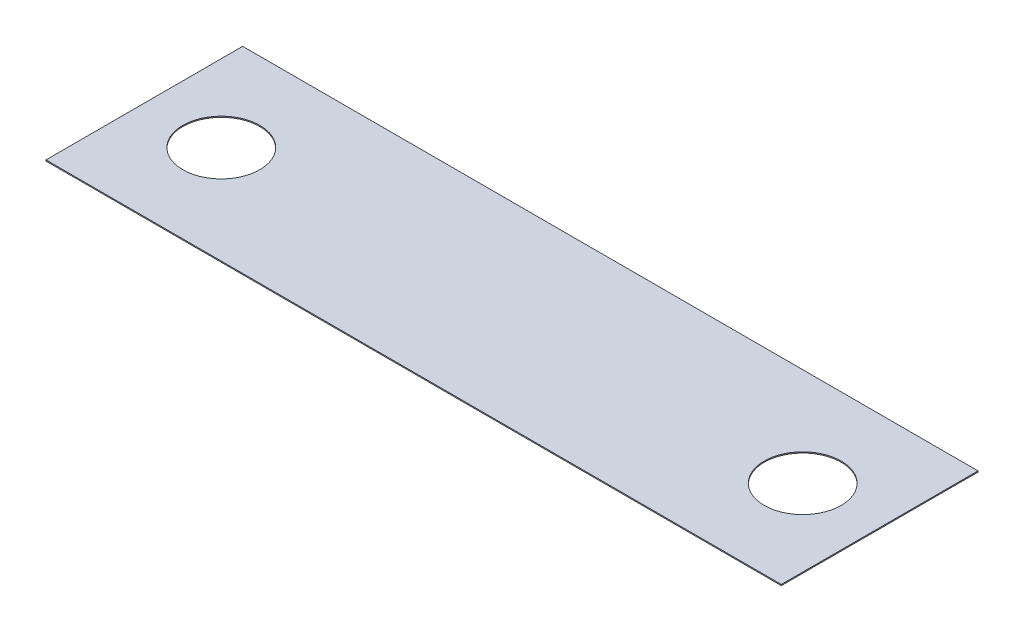
SolidWorks part; units mm, degrees
material "Low Carbon Cold Rolled"
ref_plane "Front Plane" through (0, 0, 0) normal (0, 0, 1) x (1, 0, 0)
ref_plane "Top Plane" through (0, 0, 0) normal (0, 1, 0) x (1, 0, 0)
ref_plane "Right Plane" through (0, 0, 0) normal (1, 0, 0) x (0, 0, -1)
sketch "Sketch1" plane through (0, 0, 0) normal (0, 1, 0) x (1, 0, 0)
  line L1 (0, 0) -> (86, 0)
  line L2 (0, 0) -> (0, 23)
  line L3 (0, 23) -> (86, 23)
  line L4 (86, 0) -> (86, 23)
  dimension "D1" = 86
  dimension "D2" = 23
extrude "Extrude1" add sketch "Sketch1" along normal blind 0.127
hole_wizard "Ø9.0 (9) Diameter Hole1" positions "Sketch3" profile "Sketch4" hole size "Ø9.0" standard "Ansi Metric" end condition through all
sketch "Sketch3" plane through (0, 0.127, 0) normal (0, 1, 0) x (-1, 0, 0)
  line L0 (-9, -11.5) -> (0, -11.5) construction
  line L1 (0, -23) -> (0, 0) construction
  line L3 (-77, -11.5) -> (-9, -11.5) construction
  line L5 (-43, -11.5) -> (-43, -23) construction
  line L6 (-86, -23) -> (0, -23) construction
  point P0 (-9, -11.5)
  point P1 (-77, -11.5)
  dimension "D1" = 68
sketch "Sketch4" plane through (9, 0.127, -11.5) normal (1, 0, 0) x (0, 0, 1)
  line L0 (0, 0) -> (0, 0.127)
  line L1 (0, 0.127) -> (4.5, 0.127)
  line L2 (4.5, 0.127) -> (4.5, 0)
  line L5 (4.5, 0) -> (0, 0)
  line L11 (0, -6.35) -> (0, 107.95) construction
  dimension "Thru Hole Dia." = 9
  dimension "Thru Hole Depth" = 0.127
